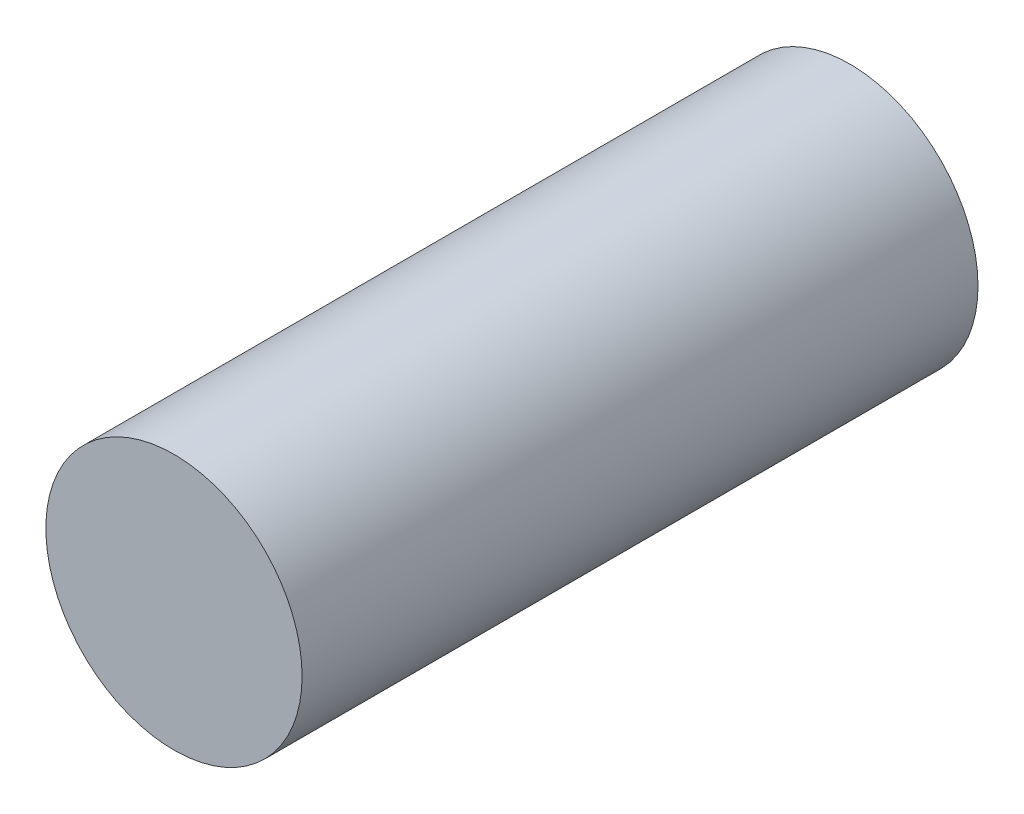
SolidWorks part; units mm, degrees
ref_plane "Front Plane" through (0, 0, 0) normal (0, 0, 1) x (1, 0, 0)
ref_plane "Top Plane" through (0, 0, 0) normal (0, 1, 0) x (1, 0, 0)
ref_plane "Right Plane" through (0, 0, 0) normal (1, 0, 0) x (0, 0, -1)
sketch "Sketch1" plane through (0, 0, 0) normal (0, 0, 1) x (1, 0, 0)
  circle A0 centre (0, 0) radius 9.25
  dimension "D1" = 18.5
extrude "Boss-Extrude1" add sketch "Sketch1" along normal blind 48.8
